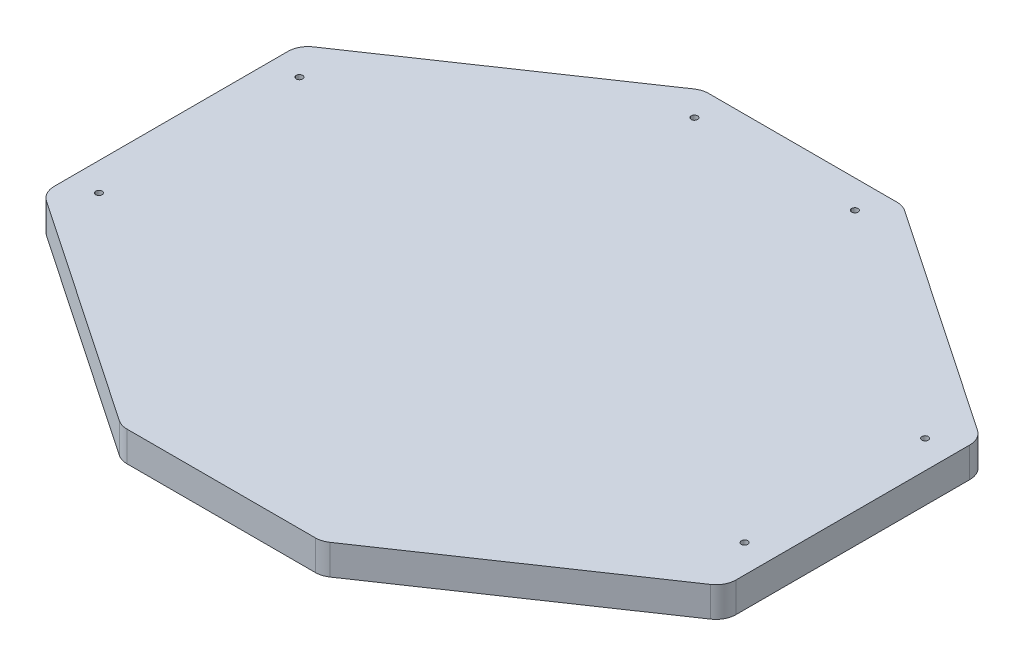
SolidWorks part; units mm, degrees
material "Balsa"
ref_plane "Plan de face" through (0, 0, 0) normal (0, 0, 1) x (1, 0, 0)
ref_plane "Plan de dessus" through (0, 0, 0) normal (0, 1, 0) x (1, 0, 0)
ref_plane "Plan de droite" through (0, 0, 0) normal (1, 0, 0) x (0, 0, -1)
sketch "Esquisse1" plane through (0, 0, 0) normal (0, 1, 0) x (1, 0, 0)
  line L0 (-76.6432, -51.4013) -> (63.3568, 43.5987)
  line L1 (63.3568, 43.5987) -> (163.3568, 43.5987)
  line L2 (-76.6432, -51.4013) -> (-76.6432, -151.4013)
  line L3 (63.3568, -246.4013) -> (163.3568, -246.4013)
  line L4 (303.3568, -51.4013) -> (303.3568, -151.4013)
  line L5 (163.3568, 43.5987) -> (303.3568, -51.4013)
  line L6 (163.3568, -246.4013) -> (303.3568, -151.4013)
  line L7 (-76.6432, -151.4013) -> (63.3568, -246.4013)
  point P0 (-76.6432, 43.5987)
  point P1 (303.3568, -246.4013)
  point P2 (-76.6432, -246.4013)
  point P3 (303.3568, 43.5987)
  dimension "D1" = 380
  dimension "D2" = 290
  dimension "D3" = 140
  dimension "D4" = 95
  dimension "D5" = 140
  dimension "D6" = 95
  dimension "D7" = 140
  dimension "D8" = 95
  dimension "D9" = 95
  dimension "D10" = 140
extrude "Boss.-Extru.1" add sketch "Esquisse1" along normal blind 15 contours L0 L1 L5 L4 L6 L3 L7 L2
fillet "Congé10" radius 10 8 edges at (303.3568, 7.5, 151.4013) (303.3568, 7.5, 51.4013) (163.3568, 7.5, -43.5987) (63.3568, 7.5, -43.5987) (-76.6432, 7.5, 51.4013) (-76.6432, 7.5, 151.4013) (63.3568, 7.5, 246.4013) (163.3568, 7.5, 246.4013)
sketch "Esquisse13" plane through (0, 15, 0) normal (0, 1, 0) x (1, 0, 0)
  line L0 (-76.6432, -56.7006) -> (-76.6432, -146.1021) construction
  line L1 (-56.6432, -173.4853) -> (-76.6432, -173.4853)
  line L2 (-56.6432, -173.4853) -> (-56.6432, -30.4519)
  line L3 (-56.6432, -30.4519) -> (-76.6432, -30.4519)
  line L4 (-76.6432, -173.4853) -> (-76.6432, -30.4519)
  line L5 (303.3568, -56.7006) -> (303.3568, -146.1021) construction
  line L6 (283.3568, -10.4047) -> (303.3568, -10.4047)
  line L7 (283.3568, -10.4047) -> (283.3568, -191.7134)
  line L8 (283.3568, -191.7134) -> (303.3568, -191.7134)
  line L9 (303.3568, -10.4047) -> (303.3568, -191.7134)
  dimension "D1" = 20
  dimension "D2" = 0
  dimension "D3" = 20
  dimension "D4" = 0
extrude "Enlèv. mat.-Extru.13" cut sketch "Esquisse13" against normal up to next
fillet "Congé12" radius 10 4 edges at (283.3568, 7.5, 37.8299) (283.3568, 7.5, 164.9728) (-56.6432, 7.5, 37.8299) (-56.6432, 7.5, 164.9728)
sketch "Esquisse14" plane through (0, 15, 0) normal (0, 1, 0) x (1, 0, 0)
  line L0 (-56.6432, -159.6735) -> (-56.6432, -43.1291) construction
  line L1 (283.3568, -43.1291) -> (283.3568, -159.6735) construction
  line L2 (66.4294, 43.5987) -> (160.2843, 43.5987) construction
  circle A0 centre (-42.6432, -51.4035) radius 1.6
  circle A1 centre (-42.6432, -151.4035) radius 1.6
  circle A2 centre (73.3593, 29.5987) radius 1.6
  circle A3 centre (153.3593, 29.5987) radius 1.6
  circle A4 centre (269.3568, -51.3991) radius 1.6
  circle A5 centre (269.3568, -141.3991) radius 1.6
  dimension "D1" = 3.2
  dimension "D2" = 3.2
  dimension "D3" = 3.2
  dimension "D4" = 3.2
  dimension "D5" = 3.2
  dimension "D6" = 3.2
  dimension "D16" = 14
  dimension "D7" = 14
  dimension "D8" = 14
  dimension "D9" = 100
  dimension "D10" = 8.27
  dimension "D11" = 14
  dimension "D12" = 14
  dimension "D13" = 90
  dimension "D14" = 8.27
  dimension "D15" = 80
  dimension "D17" = 14
  dimension "D18" = 6.925
extrude "Enlèv. mat.-Extru.14" cut sketch "Esquisse14" against normal up to next contours A2 | A3 | A4 | A0 | A1 | A5
sketch "Esquisse15" plane through (0, 15, 0) normal (0, 1, 0) x (1, 0, 0)
  line L0 (69.4108, -246.4013) -> (69.4108, 43.5987)
  line L1 (66.4294, 43.5987) -> (160.2843, 43.5987) construction
  line L2 (66.4294, -246.4013) -> (160.2843, -246.4013) construction
  dimension "D1" = 290
equation "\"D10@Esquisse14\"=(116.54-100)/2"
equation "\"D14@Esquisse14\"=8.27"
equation "\"D18@Esquisse14\"=(93.85-80)/2"
